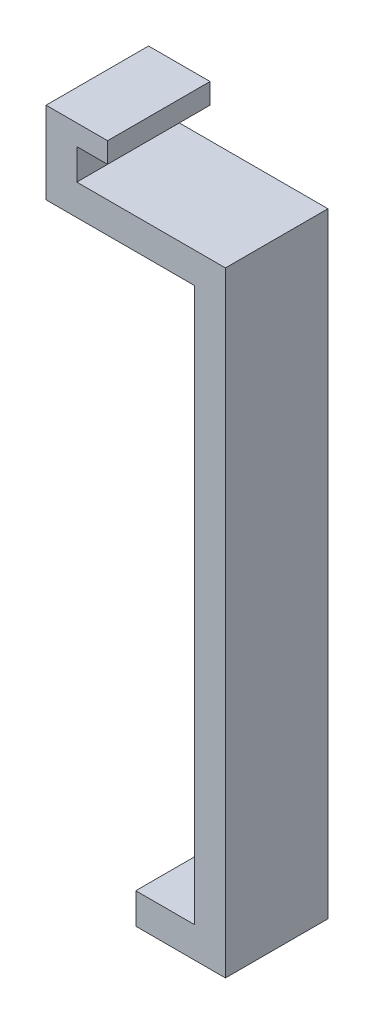
SolidWorks part; units mm, degrees
ref_plane "Alzado" through (0, 0, 0) normal (0, 0, 1) x (1, 0, 0)
ref_plane "Planta" through (0, 0, 0) normal (0, 1, 0) x (1, 0, 0)
ref_plane "Vista lateral" through (0, 0, 0) normal (1, 0, 0) x (0, 0, -1)
sketch "Croquis2" plane through (0, 0, 0) normal (0, 0, 1) x (1, 0, 0)
  line L0 (-18.2298, 32) -> (-18.2298, 24)
  line L1 (55, 0) -> (-55, 0) construction
  line L2 (-18.2298, 32) -> (-12.2298, 32)
  line L3 (-12.2298, 32) -> (-12.2298, 30)
  line L4 (-12.2298, 30) -> (-15.2298, 30)
  line L5 (-15.2298, 30) -> (-15.2298, 27)
  line L6 (-15.2298, 27) -> (-0.7298, 27)
  line L7 (-0.7298, 27) -> (-0.7298, 0)
  line L8 (-18.2298, 24) -> (-3.7298, 24)
  line L9 (-3.7298, 24) -> (-3.7298, 0)
  line L10 (-3.7298, 0) -> (-3.7298, -30)
  line L11 (-3.7298, -30) -> (-9.4798, -30)
  line L12 (-0.7298, 0) -> (-0.7298, -33)
  line L13 (-0.7298, -33) -> (-9.4798, -33)
  line L14 (-9.4798, -33) -> (-9.4798, -30)
  dimension "D1" = 2
  dimension "D2" = 3
  dimension "D3" = 3
  dimension "D4" = 3
  dimension "D5" = 3
  dimension "D6" = 3
  dimension "D7" = 14.5
  dimension "D8" = 30
  dimension "D9" = 33
  dimension "D10" = 3
extrude "Saliente-Extruir2" add sketch "Croquis2" along normal blind 10
